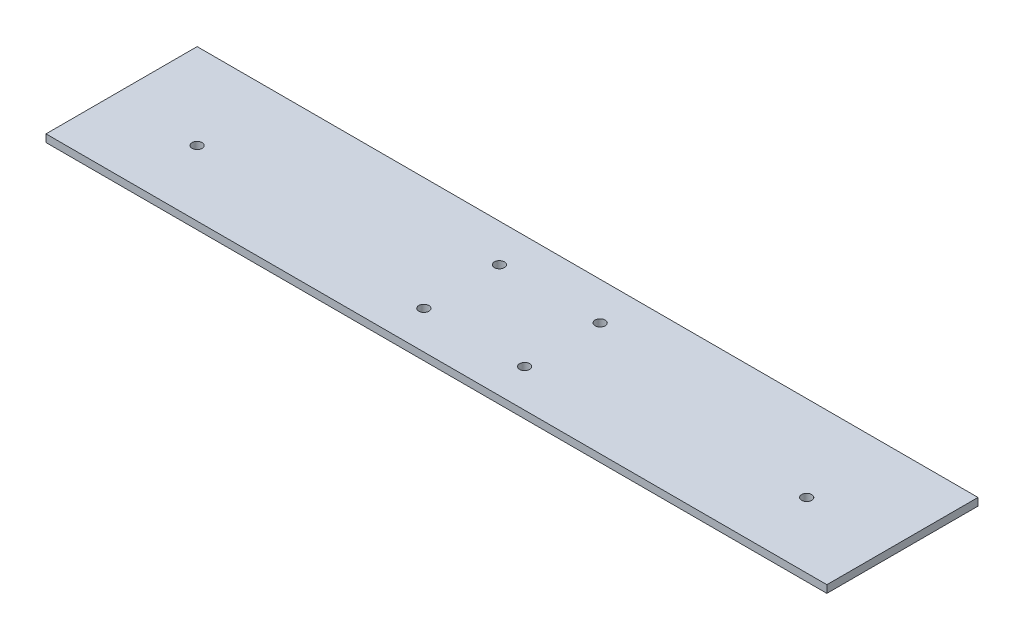
SolidWorks part; units mm, degrees
material "3.0515 (EN-AW 3103)"
ref_plane "Płaszczyzna przednia" through (0, 0, 0) normal (0, 0, 1) x (1, 0, 0)
ref_plane "Płaszczyzna górna" through (0, 0, 0) normal (0, 1, 0) x (1, 0, 0)
ref_plane "Płaszczyzna prawa" through (0, 0, 0) normal (1, 0, 0) x (0, 0, -1)
sketch "Sketch1" plane through (0, 0, 0) normal (0, 1, 0) x (1, 0, 0)
  line L1 (-10, 0) -> (300, 0)
  line L2 (-10, 0) -> (-10, 60)
  line L3 (-10, 60) -> (300, 60)
  line L4 (300, 0) -> (300, 60)
  dimension "D1" = 310
  dimension "D2" = 60
extrude "Boss-Extrude1" add sketch "Sketch1" along normal blind 3
hole_wizard "Otwór pod śrubę M41" positions "Sketch2" profile "Sketch3" hole size "M4" standard "Ansi Metric" end condition through all
sketch "Sketch2" plane through (0, 3, 0) normal (0, 1, 0) x (1, 0, 0)
  line L0 (-10, 60) -> (-10, 0) construction
  line L1 (-10, 0) -> (300, 0) construction
  line L2 (300, 0) -> (300, 60) construction
  line L3 (300, 60) -> (-10, 60) construction
  point P0 (266, 26)
  point P2 (24, 26)
  point P20 (125, 15)
  point P22 (165, 15)
  point P24 (165, 45)
  point P26 (125, 45)
  dimension "D1" = 34
  dimension "D3" = 34
  dimension "D4" = 34
  dimension "D11" = 15
  dimension "D12" = 15
  dimension "D15" = 15
  dimension "D16" = 15
  dimension "D25" = 40
  dimension "D26" = 40
  dimension "D27" = 135
  dimension "D28" = 135
  dimension "D29" = 34
sketch "Sketch3" plane through (266, 3, -26) normal (1, 0, 0) x (0, 0, 1)
  line L0 (0, 0) -> (0, 3)
  line L1 (0, 3) -> (2, 3)
  line L2 (2, 3) -> (2, 0)
  line L5 (2, 0) -> (0, 0)
  line L11 (0, -6.35) -> (0, 107.95) construction
  dimension "Œrednica otworu na wylot" = 4
  dimension "G³êbokoœæ otworu na wylot" = 3
sketch "Szkic1" plane through (0, 0, 0) normal (0, -1, 0) x (-1, 0, 0)
  circle A0 centre (-266, 26) radius 3.5
  circle A1 centre (-24, 26) radius 3.5
  dimension "D1" = 7
  dimension "D2" = 7
split line "Linia podziałowa1"
